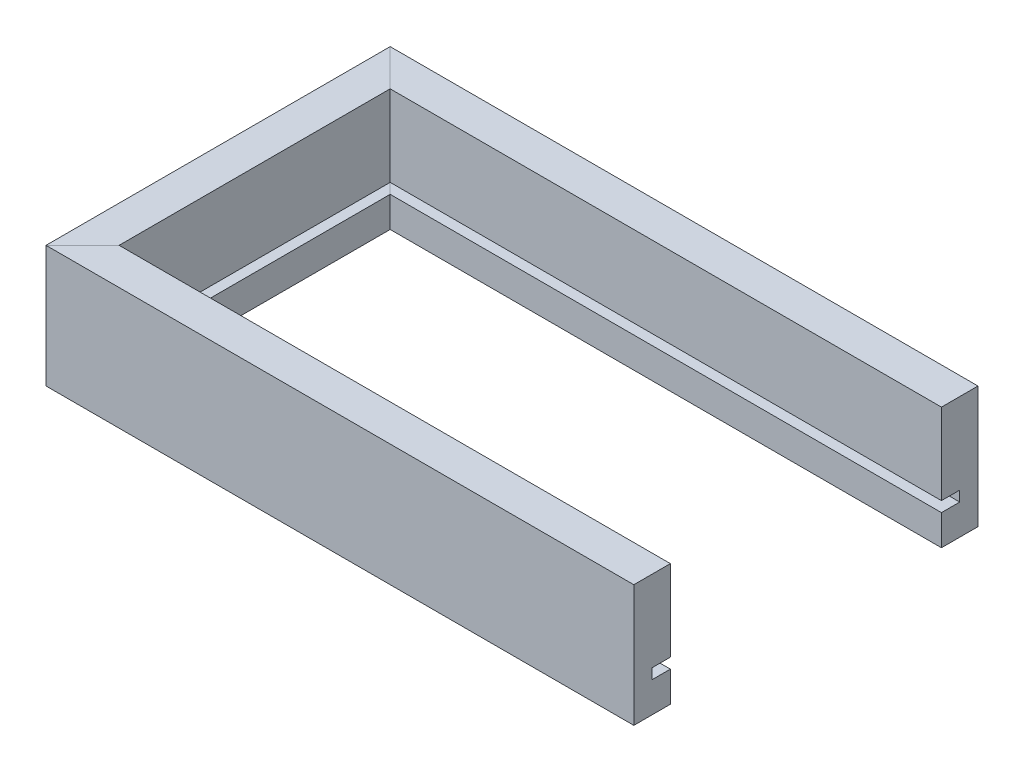
SolidWorks part; units mm, degrees
ref_plane "Front Plane" through (0, 0, 0) normal (0, 0, 1) x (1, 0, 0)
ref_plane "Top Plane" through (0, 0, 0) normal (0, 1, 0) x (1, 0, 0)
ref_plane "Right Plane" through (0, 0, 0) normal (1, 0, 0) x (0, 0, -1)
sketch "Sketch1" plane through (0, 0, 0) normal (0, 1, 0) x (1, 0, 0)
  line L1 (-46.75, -25.25) -> (46.75, -25.25)
  line L2 (-46.75, -25.25) -> (-46.75, 25.25)
  line L3 (-46.75, 25.25) -> (46.75, 25.25)
  line L5 (-46.75, -25.25) -> (46.75, 25.25) construction
  line L6 (-46.75, 25.25) -> (46.75, -25.25) construction
  point P0 (0, 0)
  point P6 (0, 0)
  point P7 (0, 0)
  dimension "D1" = 93.5
  dimension "D2" = 50.5
ref_plane "Plane1" through (46.75, 0, 0) normal (1, 0, 0) x (0, 0, -1)
sketch "Sketch2" plane through (46.75, 0, 0) normal (1, 0, 0) x (0, 0, -1)
  line L0 (-25.25, 0.85) -> (-25.25, -0.85)
  line L1 (-22.25, -0.85) -> (-25.25, -0.85)
  line L2 (-22.25, -0.85) -> (-22.25, -5.85)
  line L3 (-22.25, -5.85) -> (-28.25, -5.85)
  line L4 (-28.25, -5.85) -> (-28.25, 14.15)
  line L5 (-28.25, 14.15) -> (-22.25, 14.15)
  line L6 (-22.25, 14.15) -> (-22.25, 0.85)
  line L7 (-22.25, 0.85) -> (-25.25, 0.85)
  line L8 (-25.25, 0) -> (25.25, 0) construction
  line L9 (-25.25, 0) -> (25.25, 0) construction
  point P11 (-25.25, 0)
  point P12 (0, 0)
  dimension "D1" = 1.7
  dimension "D2" = 20
  dimension "D3" = 5
  dimension "D4" = 6
  dimension "D5" = 3
sweep "Sweep1" add profiles "Sketch2" path "Sketch1"
